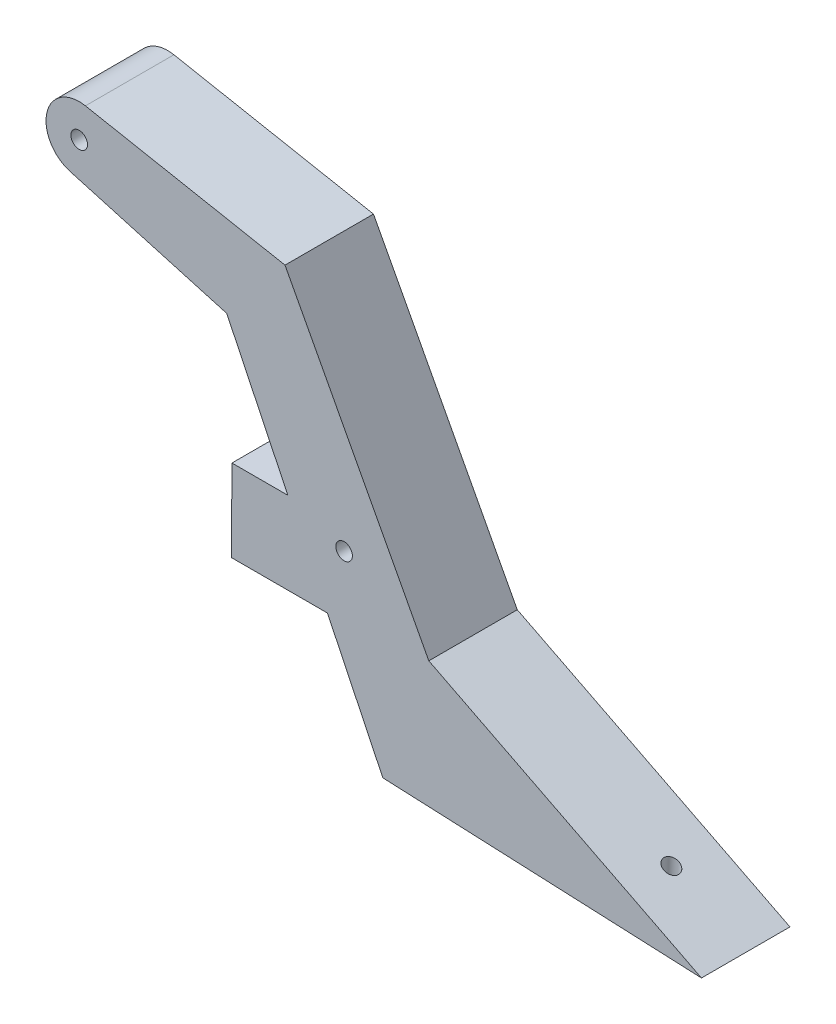
SolidWorks part; units mm, degrees
ref_plane "Front" through (0, 0, 0) normal (0, 0, 1) x (1, 0, 0)
ref_plane "Top" through (0, 0, 0) normal (0, 1, 0) x (1, 0, 0)
ref_plane "Right" through (0, 0, 0) normal (1, 0, 0) x (0, 0, -1)
sketch "草图1" plane through (0, 0, 0) normal (0, 0, 1) x (1, 0, 0)
  line L0 (1.1264, 5.8933) -> (37.221, -1.0054)
  line L1 (26.6827, -13.8357) -> (49.9154, -64.8874)
  line L2 (112.5381, -75) -> (53.3306, -72.3919)
  line L3 (63.228, -49.9799) -> (112.5381, -75)
  line L4 (49.9154, -64.8874) -> (53.3306, -72.3919)
  line L7 (26.6827, -13.8357) -> (-1.6431, -5.7706)
  line L9 (37.221, -1.0054) -> (63.228, -49.9799)
  arc A0 (1.1264, 5.8933) -> (-1.6431, -5.7706) centre (0, 0) ccw
  circle A1 centre (0, 0) radius 1.5
extrude "凸台-拉伸1" add sketch "草图1" along normal blind 16
sketch "草图2" plane through (-3.0794, -69.907, 0) normal (-0.044, -0.999, 0) x (0.999, -0.044, 0)
  circle A1 centre (66, 8) radius 1.35
  circle A2 centre (102, 8) radius 1.35
  circle A3 centre (84, 8) radius 1.35
extrude "切除-拉伸1" cut sketch "草图2" against normal blind 10
sketch "草图3" plane through (0, 0, 16) normal (0, 0, 1) x (1, 0, 0)
  line L0 (26.6827, -13.8357) -> (54.9111, -72.4615)
  line L1 (53.3306, -72.3919) -> (112.5381, -75) construction
  line L2 (54.9111, -72.4615) -> (53.3306, -72.3919)
  line L3 (53.3306, -72.3919) -> (26.6827, -13.8357)
extrude "切除-拉伸2" cut sketch "草图3" against normal blind 33
sketch "草图4" plane through (0, 0, 16) normal (0, 0, 1) x (1, 0, 0)
  line L0 (37.7391, -36.7979) -> (27.6241, -36.7979)
  line L1 (54.9111, -72.4615) -> (26.6827, -13.8357) construction
  line L2 (44.8955, -51.6606) -> (27.5321, -51.6606)
  line L3 (27.6241, -36.7979) -> (27.5321, -51.6606)
  line L4 (37.7391, -36.7979) -> (44.8955, -51.6606)
  line L5 (44.8955, -51.6606) -> (43.6725, -48.8252)
  line M1 (26.6827, -13.8357) -> (54.9111, -72.4615)
extrude "凸台-拉伸2" add sketch "草图4" against normal blind 16 contours L0 L3 L2 M1
sketch "草图5" plane through (0, 0, 16) normal (0, 0, 1) x (1, 0, 0)
  circle A0 centre (47.9111, -40.4615) radius 1.5
extrude "切除-拉伸3" cut sketch "草图5" against normal blind 24
sketch "草图7" plane through (27.8508, -0.1724, 0) normal (-1, 0.0062, 0) x (0, 0, 1)
  circle A0 centre (8, -44.016) radius 1.8
extrude "切除-拉伸5" cut sketch "草图7" against normal blind 10
